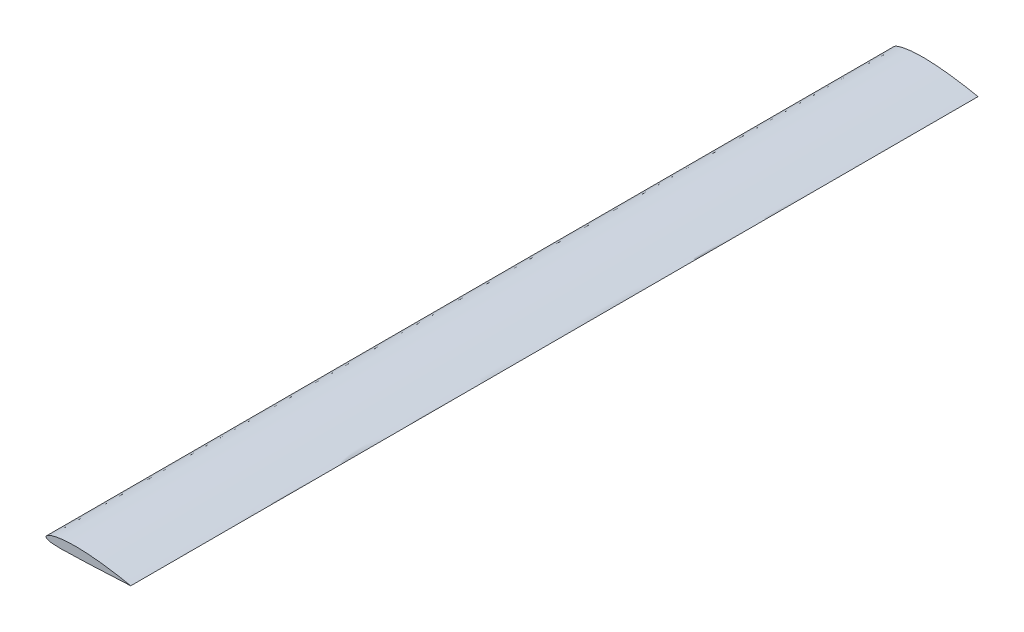
SolidWorks part; units mm, degrees
ref_plane "Front Plane" through (0, 0, 0) normal (0, 0, 1) x (1, 0, 0)
ref_plane "Top Plane" through (0, 0, 0) normal (0, 1, 0) x (1, 0, 0)
ref_plane "Right Plane" through (0, 0, 0) normal (1, 0, 0) x (0, 0, -1)
curve "Curve1"
sketch "Sketch1" plane through (0, 0, 0) normal (0, 0, 1) x (1, 0, 0)
  line L0 (0, 0) -> (1000, 0) construction
  spline S0 degree 3 poles (994.0849, -0.1038) (1001.4667, -0.1245) (994.1873, 1.0958) (988.2513, 2.6653) (973.6845, 5.6056) (955.7042, 9.4068) (932.0338, 14.1488) (903.9079, 19.5858) (871.2654, 25.6201) (834.5598, 32.0251) (794.1532, 38.635) (750.4836, 45.2845) (704.0282, 51.782) (655.278, 57.9526) (604.7669, 63.6367) (553.045, 68.6796) (500.6871, 72.9185) (448.2636, 76.2072) (396.2185, 78.5323) (345.1238, 79.394) (295.5885, 78.6174) (248.3477, 76.2263) (203.9463, 72.3334) (162.9196, 67.0588) (125.7256, 60.6171) (92.813, 53.1875) (64.5205, 45.0612) (41.1467, 36.4646) (22.8257, 27.7014) (9.6997, 18.8456) (1.4029, 9.9225) (-1.1198, -0.1347) (3.7566, -9.2736) (13.8966, -15.9025) (28.5492, -21.4363) (48.0457, -25.888) (72.2113, -29.3444) (100.8457, -31.8081) (133.644, -33.3057) (170.2707, -33.9336) (210.3336, -33.7719) (253.4349, -32.9569) (299.1344, -31.6768) (346.9879, -30.0365) (396.6487, -28.2967) (447.6224, -26.4159) (499.3541, -24.1774) (551.1525, -21.7655) (602.441, -19.2732) (652.6603, -16.7997) (701.2659, -14.3878) (747.7234, -12.125) (791.5187, -9.9844) (832.158, -8.0353) (869.1877, -6.2741) (902.2144, -4.702) (930.7442, -3.333) (954.8108, -2.2032) (973.1425, -1.2499) (987.9813, -0.7057) (994.0849, -0.1038) (1001.4667, -0.1245) (994.1873, 1.0958) knots -0.012149 -0.005431 -0.001361 0 0.001357 0.005435 0.012161 0.021476 0.033269 0.047418 0.063767 0.082121 0.102301 0.12406 0.147174 0.17138 0.196425 0.222028 0.247909 0.273781 0.29938 0.324626 0.349026 0.372326 0.394271 0.414651 0.433225 0.449841 0.464318 0.476544 0.486486 0.494145 0.49978 0.504095 0.508406 0.514029 0.521614 0.531408 0.54341 0.557546 0.573716 0.591755 0.611489 0.632714 0.65524 0.678816 0.703229 0.72842 0.753936 0.779485 0.804786 0.829557 0.853532 0.876455 0.898056 0.918108 0.93637 0.952662 0.966767 0.978537 0.987851 0.994569 0.998639 1 1.001357 1.005435 1.012161 only from (1000, 0) to (1000, 0) construction
  spline S1 degree 3 poles (994.0849, -0.1038) (1001.4667, -0.1245) (994.1873, 1.0958) (988.2513, 2.6653) (973.6845, 5.6056) (955.7042, 9.4068) (932.0338, 14.1488) (903.9079, 19.5858) (871.2654, 25.6201) (834.5598, 32.0251) (794.1532, 38.635) (750.4836, 45.2845) (704.0282, 51.782) (655.278, 57.9526) (604.7669, 63.6367) (553.045, 68.6796) (500.6871, 72.9185) (448.2636, 76.2072) (396.2185, 78.5323) (345.1238, 79.394) (295.5885, 78.6174) (248.3477, 76.2263) (203.9463, 72.3334) (162.9196, 67.0588) (125.7256, 60.6171) (92.813, 53.1875) (64.5205, 45.0612) (41.1467, 36.4646) (22.8257, 27.7014) (9.6997, 18.8456) (1.4029, 9.9225) (-1.1198, -0.1347) (3.7566, -9.2736) (13.8966, -15.9025) (28.5492, -21.4363) (48.0457, -25.888) (72.2113, -29.3444) (100.8457, -31.8081) (133.644, -33.3057) (170.2707, -33.9336) (210.3336, -33.7719) (253.4349, -32.9569) (299.1344, -31.6768) (346.9879, -30.0365) (396.6487, -28.2967) (447.6224, -26.4159) (499.3541, -24.1774) (551.1525, -21.7655) (602.441, -19.2732) (652.6603, -16.7997) (701.2659, -14.3878) (747.7234, -12.125) (791.5187, -9.9844) (832.158, -8.0353) (869.1877, -6.2741) (902.2144, -4.702) (930.7442, -3.333) (954.8108, -2.2032) (973.1425, -1.2499) (987.9813, -0.7057) (994.0849, -0.1038) (1001.4667, -0.1245) (994.1873, 1.0958) knots -0.012149 -0.005431 -0.001361 0 0.001357 0.005435 0.012161 0.021476 0.033269 0.047418 0.063767 0.082121 0.102301 0.12406 0.147174 0.17138 0.196425 0.222028 0.247909 0.273781 0.29938 0.324626 0.349026 0.372326 0.394271 0.414651 0.433225 0.449841 0.464318 0.476544 0.486486 0.494145 0.49978 0.504095 0.508406 0.514029 0.521614 0.531408 0.54341 0.557546 0.573716 0.591755 0.611489 0.632714 0.65524 0.678816 0.703229 0.72842 0.753936 0.779485 0.804786 0.829557 0.853532 0.876455 0.898056 0.918108 0.93637 0.952662 0.966767 0.978537 0.987851 0.994569 0.998639 1 1.001357 1.005435 1.012161 only from (1000, 0) to (1000, 0)
  dimension "D1" = 1000
extrude "Boss-Extrude1" add sketch "Sketch1" along normal mid plane 10000
